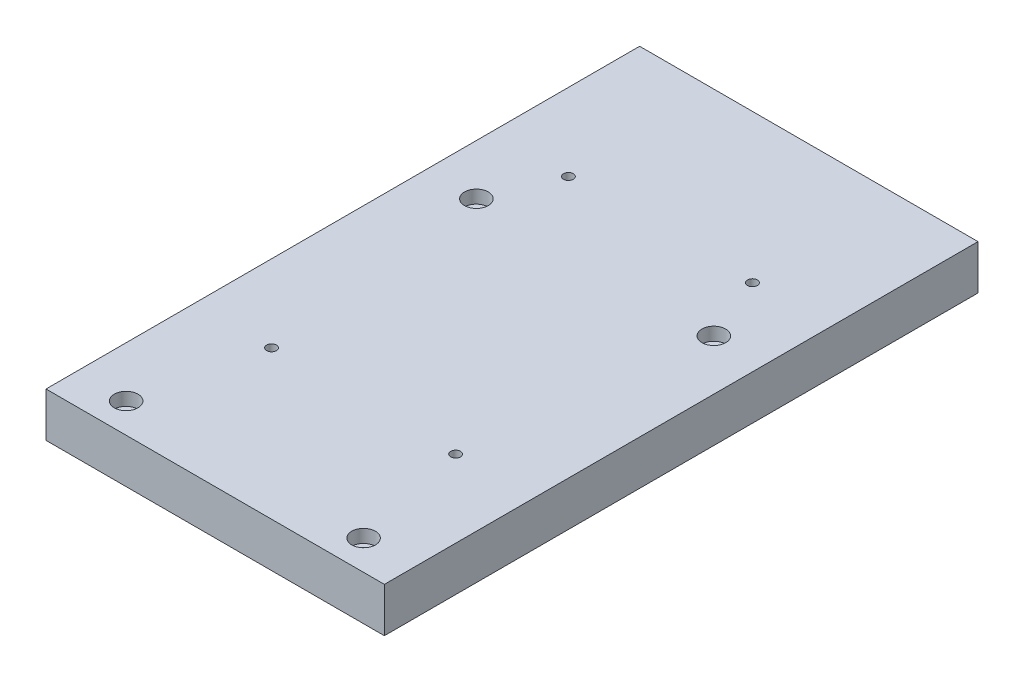
SolidWorks part; units mm, degrees
ref_plane "前视基准面" through (0, 0, 0) normal (0, 0, 1) x (1, 0, 0)
ref_plane "上视基准面" through (0, 0, 0) normal (0, 1, 0) x (1, 0, 0)
ref_plane "右视基准面" through (0, 0, 0) normal (1, 0, 0) x (0, 0, -1)
sketch "草图1" plane through (0, 0, 0) normal (0, 1, 0) x (1, 0, 0)
  line L1 (-57, 100) -> (57, 100)
  line L2 (-57, 100) -> (-57, -100)
  line L3 (-57, -100) -> (57, -100)
  line L4 (57, 100) -> (57, -100)
  line L5 (-57, 100) -> (57, -100) construction
  line L6 (-57, -100) -> (57, 100) construction
  point P0 (0, 0)
  dimension "D1" = 200
  dimension "D2" = 114
extrude "凸台-拉伸1" add sketch "草图1" along normal blind 15
hole_wizard "M4 六角凹头螺钉的柱形沉头孔1" positions "草图2" profile "草图3" counterbore size "M4" standard "ISO" end condition through all
sketch "草图2" plane through (0, 15, 0) normal (0, 1, 0) x (1, 0, 0)
  line L0 (-57, -100) -> (57, -100) construction
  line L1 (-57, 100) -> (-57, -100) construction
  point P0 (-40, -90)
  dimension "D1" = 10
  dimension "D2" = 17
sketch "草图3" plane through (-40, 15, 90) normal (1, 0, 0) x (0, 0, 1)
  line L0 (0, 0) -> (0, 15)
  line L1 (0, 15) -> (2.25, 15)
  line L3 (2.25, 15) -> (2.25, 4.4)
  line L4 (2.25, 4.4) -> (4, 4.4)
  line L5 (4, 4.4) -> (4, 0)
  line L7 (4, 0) -> (0, 0)
  line L11 (0, -6.35) -> (0, 107.95) construction
  dimension "通孔孔直径" = 4.5
  dimension "通孔孔深度" = 15
  dimension "柱形沉头孔直径" = 8
  dimension "柱形沉头孔深度" = 4.4
pattern_linear "阵列(线性)1" count 2 spacing 118 along (0, 0, -1) count 2 spacing 80 along (1, 0, 0) of "M4 六角凹头螺钉的柱形沉头孔1"
sketch "草图4" plane through (0, 15, 0) normal (0, 1, 0) x (1, 0, 0)
  line L0 (0, 108.8168) -> (0, -116.5402) construction
hole_wizard "M4 螺纹孔1" positions "草图5" profile "草图6" tap size "M4" standard "ISO"
sketch "草图5" plane through (0, 15, 0) normal (0, 1, 0) x (1, 0, 0)
  line L0 (0, 108.8168) -> (0, -116.5402) construction
  line L2 (-57, -100) -> (57, -100) construction
  point P0 (-31, -50)
  dimension "D1" = 31
  dimension "D2" = 50
sketch "草图6" plane through (-31, 15, 50) normal (1, 0, 0) x (0, 0, 1)
  line L0 (0, 0) -> (0, 11.0914)
  line L1 (0, 11.0914) -> (1.65, 10.1)
  line L2 (1.65, 10.1) -> (1.65, 0)
  line L5 (1.65, 0) -> (0, 0)
  line L10 (0, 11.0914) -> (-1.65, 10.1) construction
  line L11 (0, -6.35) -> (0, 107.95) construction
  dimension "螺纹孔钻头直径" = 3.3
  dimension "螺纹孔钻头深度" = 10.1
  dimension "导头角度" = 118
cosmetic thread "孔螺蚊线1" parameters "D1"=8, "D2"=4
pattern_linear "阵列(线性)3" count 2 spacing 100 along (0, 0, -1) count 2 spacing 62 along (1, 0, 0) of "M4 螺纹孔1"
